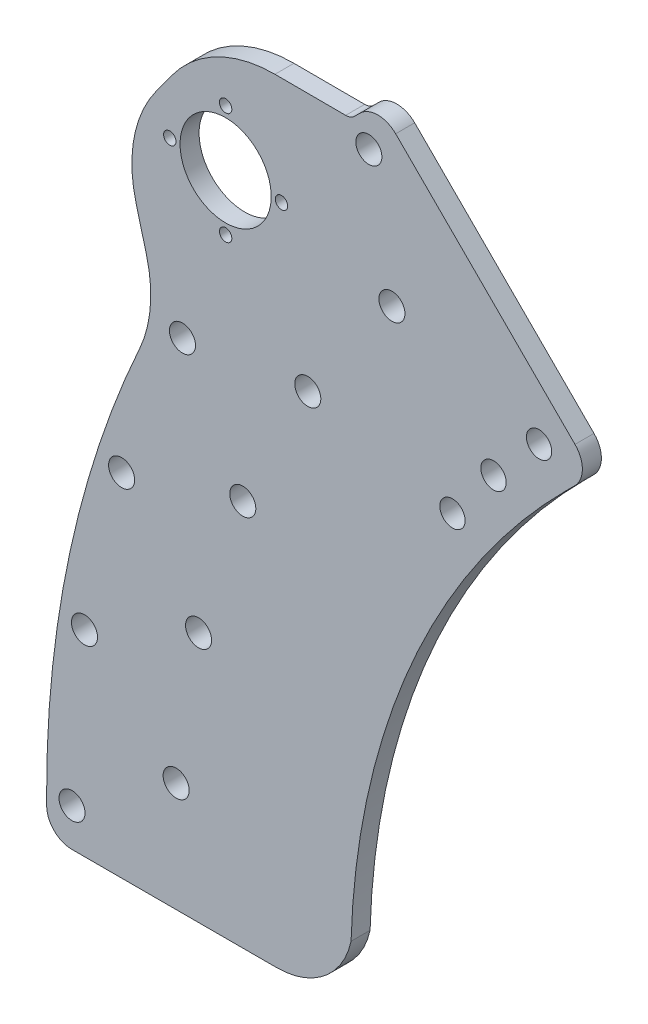
SolidWorks part; units mm, degrees
material "6061 Alloy"
ref_plane "Front Plane" through (0, 0, 0) normal (0, 0, 1) x (1, 0, 0)
ref_plane "Top Plane" through (0, 0, 0) normal (0, 1, 0) x (1, 0, 0)
ref_plane "Right Plane" through (0, 0, 0) normal (1, 0, 0) x (0, 0, -1)
sketch "Sketch1" plane through (0, 0, 0) normal (0, 0, 1) x (1, 0, 0)
  line L0 (-260.35, 0) -> (-184.15, 0) construction
  line L1 (-184.0953, 184.0953) -> (-130.2137, 130.2137) construction
  line L2 (-184.0953, 184.0953) -> (-202.0558, 166.1347) construction
  line L3 (-260.35, 0) -> (-260.35, -3.2004)
  line L4 (-254.0254, -9.525) -> (-190.4746, -9.525)
  line L5 (-184.15, -3.2004) -> (-184.15, 0)
  line L6 (-183.1616, 185.0289) -> (-181.8322, 186.3583)
  line L7 (-130.2137, 130.2137) -> (-127.9507, 132.4767)
  line L8 (-127.9507, 141.4211) -> (-172.8879, 186.3583)
  line L9 (-227.8953, 17.9357) -> (0, 0) construction
  line L10 (0, 0) -> (-227.8953, 17.9357) construction
  line L11 (0, 0) -> (-222.2838, 53.3656) construction
  line L12 (-185.4156, 184.0989) -> (-203.1409, 184.1485)
  line L13 (-228.8843, 171.1042) -> (-232.8995, 165.5974)
  line L14 (-237.9513, 138.8186) -> (-235.3027, 128.7445)
  line L15 (-230.8919, 168.3508) -> (-210.3682, 153.3863) construction
  line L16 (-224.0889, 134.5684) -> (-196.6474, 172.2042) construction
  circle A0 centre (0, 0) radius 184.15 construction
  arc A1 (-130.2137, 130.2137) -> (-184.15, 0) centre (0, 0) ccw
  arc A13 (-260.35, -3.2004) -> (-254.0254, -9.525) centre (-254.0254, -3.2004) ccw
  arc A14 (-184.15, -3.2004) -> (-190.4746, -9.525) centre (-190.4746, -3.2004) cw
  arc A15 (-172.8879, 186.3583) -> (-181.8322, 186.3583) centre (-177.3601, 181.8861) ccw
  arc A16 (-127.9507, 141.4211) -> (-127.9507, 132.4767) centre (-132.4229, 136.9489) cw
  circle A17 centre (0, 0) radius 193.675 construction
  circle A18 centre (-158.6493, 111.0874) radius 3.175
  circle A19 centre (-148.3637, 124.4919) radius 3.175
  circle A20 centre (-136.9489, 136.9489) radius 3.175
  circle A21 centre (-227.8953, 17.9357) radius 3.2639
  circle A22 centre (-222.2838, 53.3656) radius 3.2639
  circle A23 centre (-211.1989, 87.4814) radius 3.2639
  circle A24 centre (-194.9135, 119.4432) radius 3.2639
  circle A25 centre (-173.8288, 148.4638) radius 3.2639
  arc A26 (-260.35, 0) -> (-237.0951, 107.5549) centre (0, 0) cw
  circle A27 centre (-215.4991, 157.1274) radius 14 construction
  arc A28 (-210.3682, 153.3863) -> (-184.0953, 184.0953) centre (0, 0) cw construction
  circle A29 centre (-215.4991, 171.1274) radius 1.55
  circle A30 centre (-201.4991, 157.1274) radius 1.55
  circle A31 centre (-215.4991, 143.1274) radius 1.55
  circle A32 centre (-229.4991, 157.1274) radius 1.55
  circle A33 centre (-215.4991, 157.1274) radius 11.43
  arc A34 (-183.1616, 185.0289) -> (-185.4156, 184.0989) centre (-185.4067, 187.2739) cw
  arc A35 (-237.0951, 107.5549) -> (-235.3027, 128.7445) centre (-266.0091, 120.6713) ccw
  arc A36 (-237.9513, 138.8186) -> (-232.8995, 165.5974) centre (-207.2448, 146.8918) cw
  arc A37 (-203.1409, 184.1485) -> (-228.8843, 171.1042) centre (-203.2296, 152.3986) ccw
  circle A38 centre (-254, 0) radius 3.2639
  circle A39 centre (-250.8728, 39.7344) radius 3.2639
  circle A40 centre (-241.5684, 78.4903) radius 3.2639
  circle A41 centre (-226.3157, 115.3136) radius 3.2639
  circle A43 centre (-179.6051, 179.6051) radius 3.2639
  circle A44 centre (-205.4903, 149.2975) radius 3.2639 [skipped]
  point P15 (-210.3682, 153.3863)
  point P26 (-260.35, -9.525)
  point P33 (-177.3601, 190.8304)
  point P53 (0, 0)
  point P61 (-215.4991, 157.1274)
  point P65 (-232.3397, 117.475)
  point P68 (-241.7871, 153.4081)
  point P71 (-219.3403, 184.1937)
  point P83 (0, 0)
  dimension "D1" = 368.3
  dimension "D5" = 28
  dimension "D9" = 6.3246
  dimension "D11" = 6.3246
  dimension "D12" = 193.675
  dimension "D13" = 6.35
  dimension "D16" = 228.6
  dimension "D21" = 25.4
  dimension "D23" = 127
  dimension "D4" = 6.5278
  dimension "D24" = 3.1
  dimension "D26" = 22.86
  dimension "D27" = 3.175
  dimension "D28" = 31.75
  dimension "D29" = 69.85
  dimension "D30" = 6.5278
  dimension "D32" = 9
  dimension "D2" = 45
  dimension "D3" = 76.2
  dimension "D7" = 50.8
  dimension "D8" = 9.525
  dimension "D10" = 9.525
  dimension "D14" = 5
  dimension "D15" = 10
  dimension "D17" = 4.5
  dimension "D19" = 45
  dimension "D20" = 9
  dimension "D22" = 38.1
  dimension "D25" = 4
  dimension "D6" = 266.7
  dimension "D18" = 5
  dimension "D31" = 6
extrude "Boss-Extrude1" add sketch "Sketch1" along normal blind 4.7625
sketch "Sketch2" plane through (0, 0, 4.7625) normal (0, 0, 1) x (1, 0, 0)
  line L1 (-202.692, -9.525) -> (-183.642, -9.525)
  line L2 (-254.0254, -9.525) -> (-190.4746, -9.525) construction
  line L3 (-183.642, -9.525) -> (-183.642, 9.525)
  line L4 (-202.692, 9.525) -> (-202.692, -9.525) construction
  line L5 (-202.692, 9.525) -> (-183.642, 9.525) construction
  arc A2 (-202.692, -9.525) -> (-183.642, 9.525) centre (-202.692, 9.525) ccw
  dimension "D1" = 38.1
  dimension "D2" = 0.508
extrude "Cut-Extrude1" cut sketch "Sketch2" against normal through all
